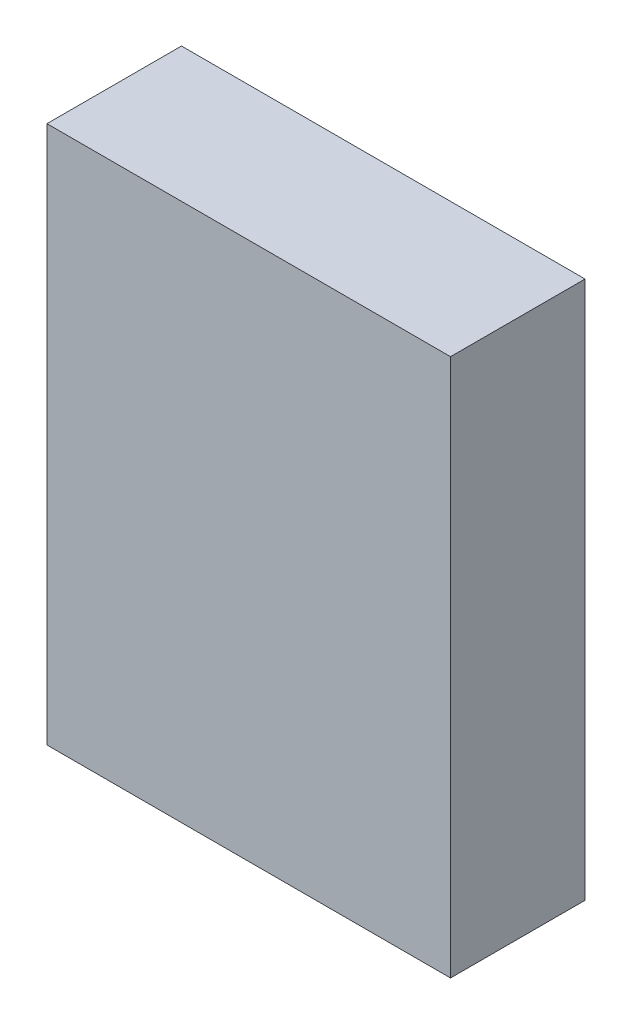
SolidWorks part; units mm, degrees
ref_plane "Front Plane" through (0, 0, 0) normal (0, 0, 1) x (1, 0, 0)
ref_plane "Top Plane" through (0, 0, 0) normal (0, 1, 0) x (1, 0, 0)
ref_plane "Right Plane" through (0, 0, 0) normal (1, 0, 0) x (0, 0, -1)
sketch "Sketch1" plane through (0, 0, 0) normal (0, 0, 1) x (1, 0, 0)
  line L1 (0, 0) -> (6, 0)
  line L2 (0, 0) -> (0, 8)
  line L3 (0, 8) -> (6, 8)
  line L4 (6, 0) -> (6, 8)
  dimension "D1" = 6
  dimension "D2" = 8
extrude "Profile" add sketch "Sketch1" along normal blind 2
equation "\"Profile_Depth\"= 2mm"
equation "\"D1@Profile\" = \"Profile_Depth\""
equation "\"Profile_Sketch_1\"= 6mm"
equation "\"D1@Sketch1\" = \"Profile_Sketch_1\""
equation "\"Profile_Sketch_2\"= 8mm"
equation "\"D2@Sketch1\" = \"Profile_Sketch_2\""
equation "\"EnvelopeWidth\"= 6mm"
equation "\"EnvelopeHeight\"= 8mm"
